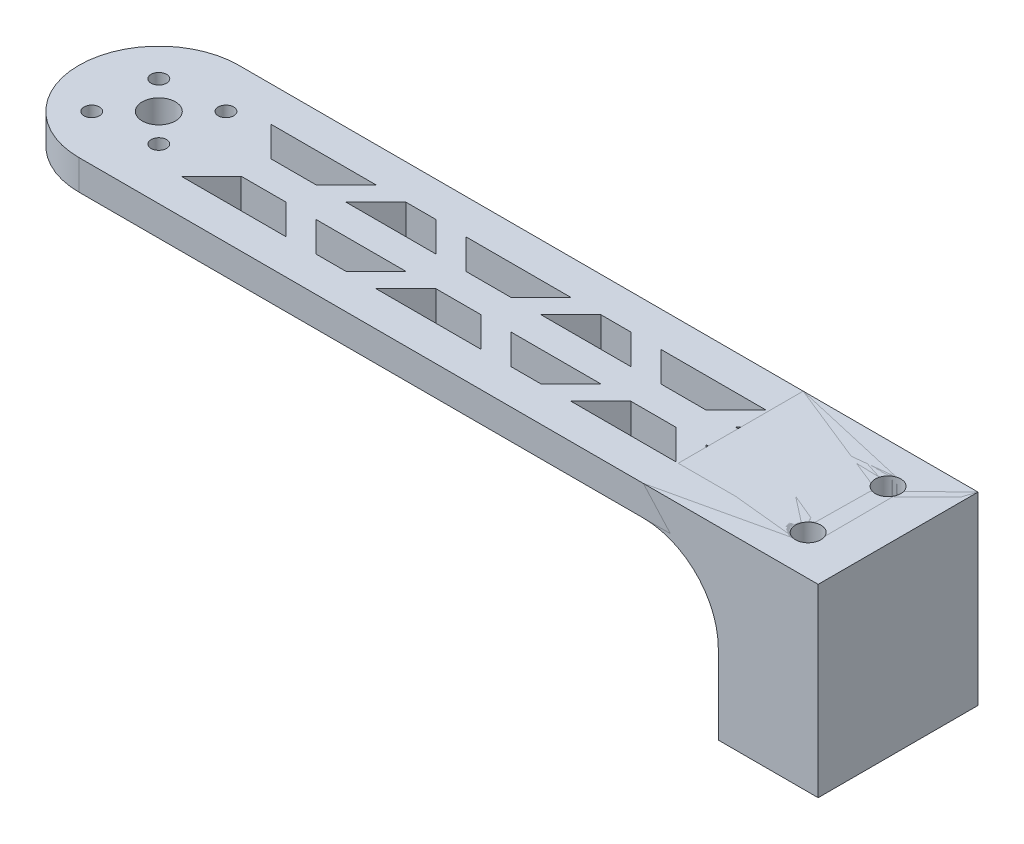
SolidWorks part; units mm, degrees
material "Custom Plastic"
ref_plane "Front Plane" through (0, 0, 0) normal (0, 0, 1) x (1, 0, 0)
ref_plane "Top Plane" through (0, 0, 0) normal (0, 1, 0) x (1, 0, 0)
ref_plane "Right Plane" through (0, 0, 0) normal (1, 0, 0) x (0, 0, -1)
sketch "Sketch1" plane through (0, 0, 0) normal (0, 1, 0) x (1, 0, 0)
  line L0 (0, -16) -> (148, -16)
  line L1 (0, 16) -> (148, 16)
  line L3 (148, 16) -> (148, -16)
  arc A0 (0, 16) -> (0, -16) centre (0, 0) ccw
  point P1 (0, 0)
  point P2 (0, -16)
  point P3 (0, 0)
  point P8 (148, -16)
  point P10 (148, 16)
  point P11 (148, -16)
  dimension "D2" = 16
  dimension "D3" = 32
  dimension "D1" = 148
extrude "Boss-Extrude1" add sketch "Sketch1" against normal blind 6
sketch "Sketch11" plane through (0, 0, 0) normal (0, 1, 0) x (1, 0, 0)
  line L0 (0, 0) -> (148, 0) construction
  line L1 (148, -16) -> (148, 16) construction
  line L2 (13.5, 9) -> (19.5, 3)
  line L3 (19.5, 3) -> (28.5, 3)
  line L4 (28.5, 3) -> (34.5, 9)
  line L5 (34.5, 9) -> (13.5, 9)
  line L6 (52.5, 3) -> (46.5, 9)
  line L7 (46.5, 9) -> (40.5, 9)
  line L8 (40.5, 9) -> (34.5, 3)
  line L9 (34.5, 3) -> (52.5, 3)
  line L10 (24, 9) -> (24, 3) construction
  line L11 (52.5, 9) -> (58.5, 3)
  line L12 (73.5, 9) -> (52.5, 9)
  line L13 (67.5, 3) -> (73.5, 9)
  line L14 (58.5, 3) -> (67.5, 3)
  line L15 (91.5, 9) -> (97.5, 3)
  line L16 (112.5, 9) -> (91.5, 9)
  line L17 (106.5, 3) -> (112.5, 9)
  line L18 (97.5, 3) -> (106.5, 3)
  line L24 (73.5, 3) -> (91.5, 3)
  line L25 (145.5, 3) -> (151.5, 9) [skipped]
  line L26 (79.5, 9) -> (73.5, 3)
  line L27 (85.5, 9) -> (79.5, 9)
  line L28 (91.5, 3) -> (85.5, 9)
  line L29 (112.5, 3) -> (130.5, 3)
  line L30 (118.5, 9) -> (112.5, 3)
  line L31 (124.5, 9) -> (118.5, 9)
  line L32 (130.5, 3) -> (124.5, 9)
  line L33 (130.5, 9) -> (136.5, 3) [skipped]
  line L34 (139.5, 9) -> (130.5, 9) [skipped]
  line L35 (136.5, 3) -> (139.5, 3) [skipped]
  point P15 (24, 3)
  dimension "D1" = 6
  dimension "D2" = 21
  dimension "D3" = 45
  dimension "D4" = 45
  dimension "D5" = 24
  dimension "D6" = 3
  dimension "D7" = 45
  dimension "D8" = 45
  dimension "D9" = 6
  dimension "D10" = 18
  dimension "D11" = 3
  dimension "D12" = 6
  dimension "D13" = 4
  dimension "D14" = 6
  dimension "D16" = 6
  dimension "D15" = 3
extrude "Cut-Extrude3" cut sketch "Sketch11" against normal up to next
mirror "Mirror1" about plane through (0, 0, 0) normal (0, 0, 1) of "Cut-Extrude3"
sketch "Sketch14" plane through (0, 0, 0) normal (0, 0, 1) x (1, 0, 0)
  line L0 (148, -6) -> (148, -37)
  line L1 (148, -37) -> (128, -37)
  line L5 (128, -37) -> (128, -21)
  line L6 (0, -6) -> (148, -6) construction
  line L8 (113, -6) -> (113, 0)
  line L9 (0, 0) -> (148, 0) construction
  line L10 (113, 0) -> (148, 0)
  line L11 (148, 0) -> (148, -6)
  arc A0 (128, -21) -> (113, -6) centre (113, -21) ccw
  dimension "D4" = 15
  dimension "D1" = 31
  dimension "D2" = 20
  dimension "D3" = 16
extrude "Boss-Extrude12" add sketch "Sketch14" along normal mid plane 32 separate body
sketch "Sketch8" plane through (0, 0, 0) normal (0, 1, 0) x (1, 0, 0)
  line L0 (148, -16) -> (148, 16) construction
  line L1 (148, 16) -> (0, 16) construction
  line L2 (0, -16) -> (148, -16) construction
  circle A0 centre (138, 8) radius 2.55
  circle A1 centre (138, -8) radius 2.55
  dimension "D1" = 5.1
  dimension "D2" = 10
  dimension "D4" = 8
  dimension "D5" = 16
  dimension "D6" = 10
  dimension "D3" = 8
extrude "Cut-Extrude4" cut sketch "Sketch8" against normal through all
ref_plane "Plane1" through (0, -37, 0) normal (0, -1, 0) x (-1, 0, 0)
sketch "Sketch16" plane through (0, -37, 0) normal (0, -1, 0) x (-1, 0, 0)
  line L0 (-148, 16) -> (-148, 36)
  line L1 (-148, 36) -> (-128, 16)
  line L2 (-148, 16) -> (-128, 16)
  line L3 (-3.3, 0) -> (3.3, 0) construction
  line L4 (-148, -16) -> (-128, -16)
  line L5 (-148, -36) -> (-128, -16)
  line L6 (-148, -16) -> (-148, -36)
  dimension "D1" = 20
sketch "Sketch10" plane through (0, 0, 0) normal (0, 1, 0) x (1, 0, 0)
  line L0 (-9.5, 0) -> (9.5, 0) construction
  line L1 (0, 0) -> (6.7175, 6.7175) construction
  line L2 (-5.6569, 5.6569) -> (0, 0) construction
  line L3 (-6.7175, -6.7175) -> (0, 0) construction
  line L4 (0, 0) -> (5.6569, -5.6569) construction
  circle A0 centre (0, 0) radius 9.5 construction
  circle A1 centre (0, 0) radius 8 construction
  circle A2 centre (-6.7175, -6.7175) radius 1.55
  circle A3 centre (6.7175, 6.7175) radius 1.55
  circle A4 centre (5.6569, -5.6569) radius 1.55
  circle A5 centre (-5.6569, 5.6569) radius 1.55
  circle A6 centre (0, 0) radius 3.325
  dimension "D1" = 19
  dimension "D2" = 16
  dimension "D3" = 3.1
  dimension "D8" = 6.65
  dimension "D4" = 45
  dimension "D5" = 45
  dimension "D6" = 45
  dimension "D7" = 45
extrude "Cut-Extrude2" cut sketch "Sketch10" against normal up to next (6 mm away)
equation "\"arm-width\"= 32"
equation "\"D2@Sketch1\"=\"arm-width\"/2"
equation "\"arm-length\"=148"
equation "\"D3@Sketch1\"=\"arm-width\""
equation "\"D1@Boss-Extrude12\"=\"arm-width\""
